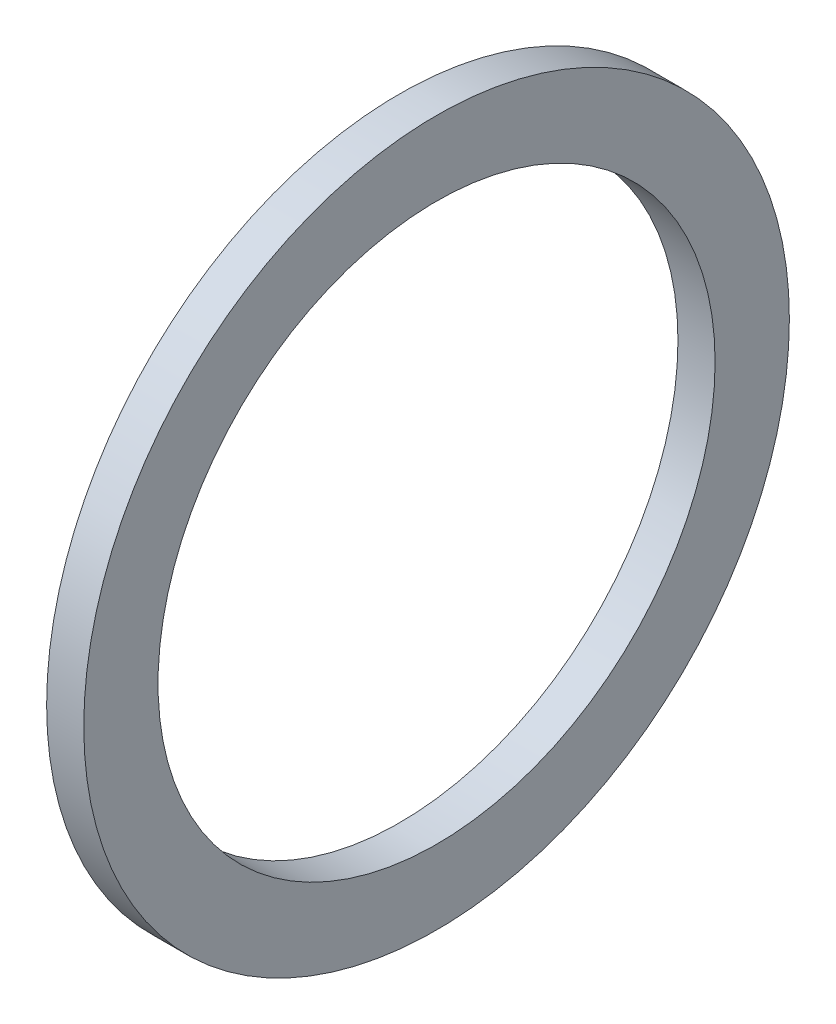
SolidWorks part; units mm, degrees
material "3.3523 (EN-AW 5052)"
ref_plane "Спереди" through (0, 0, 0) normal (0, 0, 1) x (1, 0, 0)
ref_plane "Сверху" through (0, 0, 0) normal (0, 1, 0) x (1, 0, 0)
ref_plane "Справа" through (0, 0, 0) normal (1, 0, 0) x (0, 0, -1)
sketch "Эскиз1" plane through (0, 0, 0) normal (1, 0, 0) x (0, 0, -1)
  line L0 (0, 47.5) -> (0, 37.5) construction
  circle A0 centre (0, 0) radius 37.5
  circle A1 centre (0, 0) radius 47.5
  point P48 (0, 0)
  dimension "D1" = 75
  dimension "D2" = 95
extrude "Бобышка-Вытянуть1" add sketch "Эскиз1" along normal blind 5
